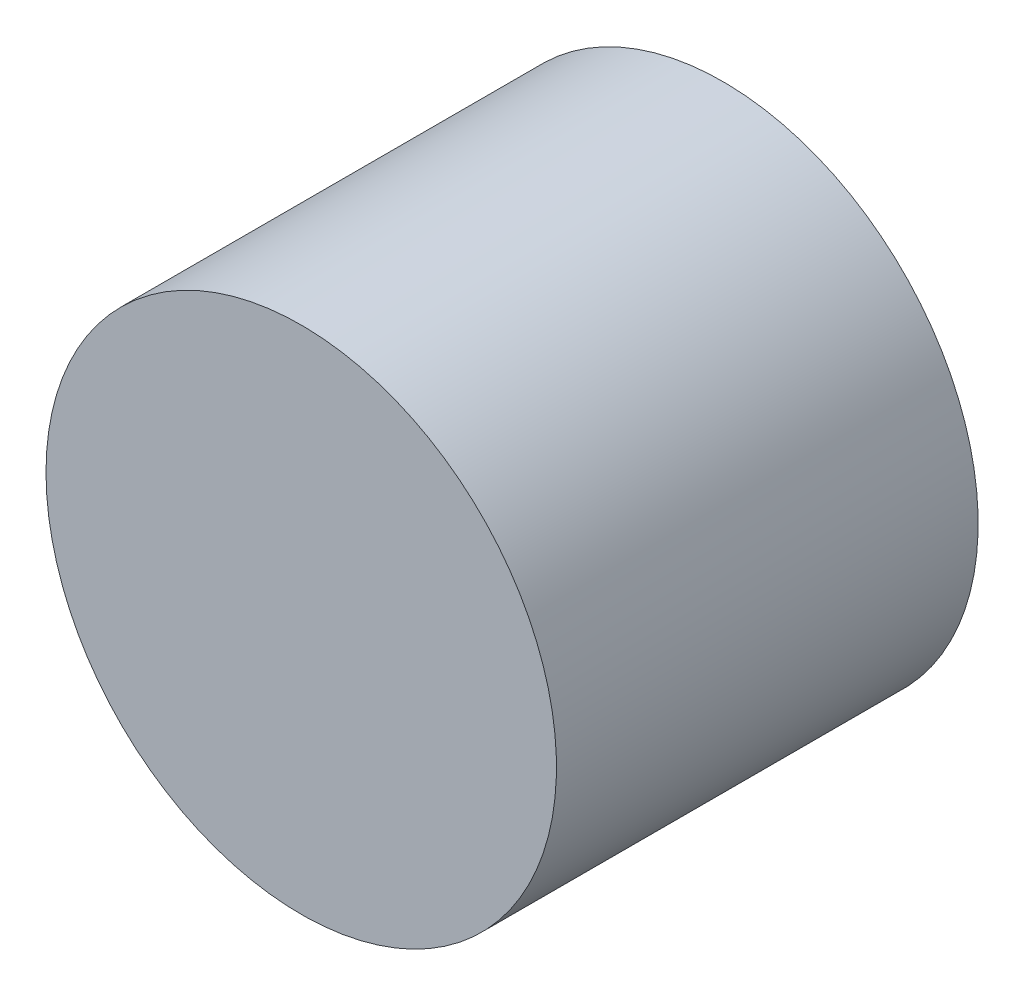
SolidWorks part; units mm, degrees
ref_plane "Спереди" through (0, 0, 0) normal (0, 0, 1) x (1, 0, 0)
ref_plane "Сверху" through (0, 0, 0) normal (0, 1, 0) x (1, 0, 0)
ref_plane "Справа" through (0, 0, 0) normal (1, 0, 0) x (0, 0, -1)
other "Configuration Table"
sketch "Эскиз2" plane through (0, 0, 0) normal (0, 0, 1) x (1, 0, 0)
  circle A0 centre (0, 0) radius 2.3
  dimension "D1" = 4.6
extrude "Бобышка-Вытянуть1" add sketch "Эскиз2" along normal blind 3.8
